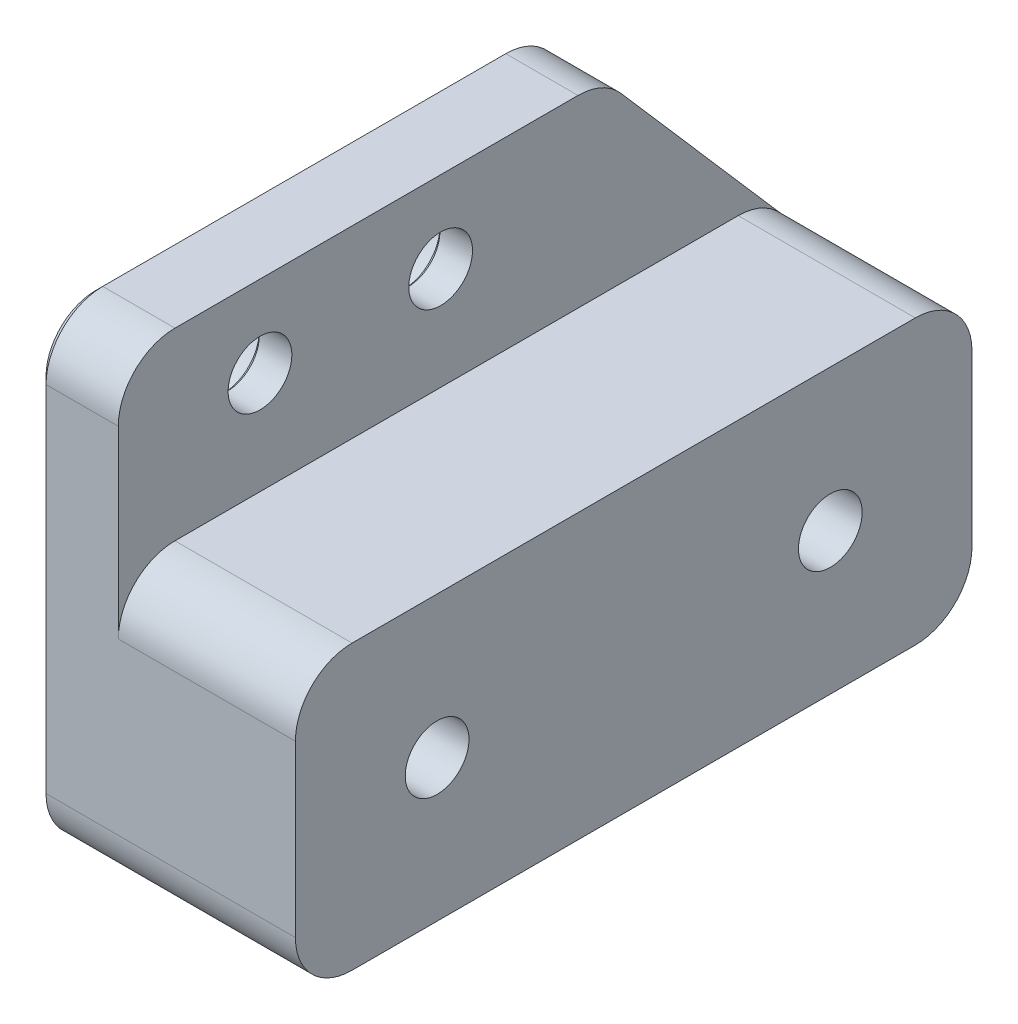
SolidWorks part; units mm, degrees
ref_plane "Front Plane" through (0, 0, 0) normal (0, 0, 1) x (1, 0, 0)
ref_plane "Top Plane" through (0, 0, 0) normal (0, 1, 0) x (1, 0, 0)
ref_plane "Right Plane" through (0, 0, 0) normal (1, 0, 0) x (0, 0, -1)
sketch "Sketch1" plane through (0, 0, 0) normal (1, 0, 0) x (0, 0, -1)
  line L0 (0, -10) -> (0, 23) construction
  line L1 (37.75, 0) -> (-10, 0) construction
  line L2 (-6, -10) -> (33.75, -10)
  line L3 (37.75, -6) -> (37.75, 6)
  line L4 (22.4457, 23) -> (-6, 23)
  line L6 (-10, 19) -> (-10, -6)
  line L7 (12.75, 17.25) -> (27.75, 0) construction
  line L8 (0, 17.25) -> (12.75, 17.25) construction
  line L9 (25.4641, 21.6247) -> (36.7684, 8.6247)
  circle A0 centre (0, 0) radius 2 construction
  circle A1 centre (0, 17.25) radius 2 construction
  circle A2 centre (27.75, 0) radius 2.25
  circle A3 centre (0, 17.25) radius 2.25
  circle A4 centre (0, 0) radius 2.25
  arc A5 (33.75, -10) -> (37.75, -6) centre (33.75, -6) ccw
  arc A7 (-6, 23) -> (-10, 19) centre (-6, 19) ccw
  arc A9 (-10, -6) -> (-6, -10) centre (-6, -6) ccw
  circle A10 centre (12.75, 17.25) radius 2.25
  arc A11 (22.4457, 23) -> (25.4641, 21.6247) centre (22.4457, 19) cw
  arc A12 (36.7684, 8.6247) -> (37.75, 6) centre (33.75, 6) cw
  point P35 (37.75, 0)
  dimension "D2" = 4
  dimension "D3" = 4
  dimension "D8" = 4
  dimension "D6" = 17.25
  dimension "D9" = 5.75
  dimension "D11" = 10
  dimension "D5" = 10
  dimension "D7" = 12.75
  dimension "D10" = 10
  dimension "D12" = 15
  dimension "D1" = 0.25
  dimension "D4" = 0.25
extrude "Boss-Extrude1" add sketch "Sketch1" along normal blind 2.6
sketch "Sketch3" plane through (0, 0, 0) normal (1, 0, 0) x (0, 0, -1)
  line L5 (-6, -10) -> (33.75, -10)
  line L6 (37.75, -6) -> (37.75, 6)
  line L7 (22.4457, 23) -> (-6, 23)
  line L8 (36.7684, 8.6247) -> (25.4641, 21.6247)
  line L9 (-10, 19) -> (-10, -6)
  line L10 (-6, -10) -> (33.75, -10)
  line L11 (37.75, -6) -> (37.75, 6)
  line L12 (22.4457, 23) -> (-6, 23)
  line L14 (-10, 19) -> (-10, -6)
  line L20 (36.7684, 8.6247) -> (25.4641, 21.6247)
  circle A0 centre (0, 0) radius 3.5 construction
  circle A1 centre (27.75, 0) radius 3.75
  circle A2 centre (27.75, 0) radius 2.25 construction
  circle A3 centre (0, 0) radius 2.25 construction
  circle A4 centre (0, 0) radius 3.75
  arc A5 (-10, -6) -> (-6, -10) centre (-6, -6) ccw
  arc A6 (33.75, -10) -> (37.75, -6) centre (33.75, -6) ccw
  arc A7 (37.75, 6) -> (36.7684, 8.6247) centre (33.75, 6) ccw
  arc A8 (-6, 23) -> (-10, 19) centre (-6, 19) ccw
  arc A9 (37.75, 6) -> (36.7684, 8.6247) centre (33.75, 6) ccw
  arc A10 (-10, -6) -> (-6, -10) centre (-6, -6) ccw
  arc A11 (33.75, -10) -> (37.75, -6) centre (33.75, -6) ccw
  arc A13 (-6, 23) -> (-10, 19) centre (-6, 19) ccw
  circle A15 centre (0, 17.25) radius 3.75
  circle A16 centre (0, 17.25) radius 2.25 construction
  circle A18 centre (12.75, 17.25) radius 3.75
  circle A19 centre (12.75, 17.25) radius 2.25 construction
  arc A22 (25.4641, 21.6247) -> (22.4457, 23) centre (22.4457, 19) ccw
  arc A23 (25.4641, 21.6247) -> (22.4457, 23) centre (22.4457, 19) ccw
  dimension "D2" = 7
  dimension "D3" = 0.25
extrude "Boss-Extrude3" add sketch "Sketch3" against normal blind 3
chamfer "Chamfer2" distance 0.3 angle 45 8 edges at (0, 0, -31.5) (0, 0, -30) (0, 0, -3.75) (0, 0, -2.25) (0, 17.25, -2.25) (0, 17.25, -3.75) (0, 17.25, -16.5) (0, 17.25, -15)
chamfer "Chamfer3" distance 0.5 angle 45 14 edges at (-3, 0, -3.75) (-3, 6.5, 10) (-3, 21.8284, 8.8284) (-3, 23, -8.2228) (-3, 0, -37.75) (-3, -8.8284, -36.5784) (-3, -10, -13.875) (-3, -8.8284, 8.8284) (-3, 0, -31.5) (-3, 17.25, -3.75) (-3, 7.4011, -37.4966) (-3, 15.1247, -31.1162) (-3, 22.64, -24.1041) (-3, 17.25, -16.5)
sketch "Sketch4" plane through (2.6, 0, 0) normal (1, 0, 0) x (0, 0, -1)
  line L0 (-6, -10) -> (33.75, -10) construction
  line L1 (-6, -10) -> (33.75, -10)
  line L2 (-25, 0) -> (10, 0) construction
  line L6 (37.75, -6) -> (37.75, 6)
  line L7 (-6, 10) -> (33.75, 10)
  line L8 (37.75, -6) -> (37.75, 6) construction
  line L9 (-10, -6) -> (-10, 6)
  line L10 (-10, 19) -> (-10, -6) construction
  circle A0 centre (0, 0) radius 2.25 construction
  circle A1 centre (27.75, 0) radius 2.25 construction
  arc A2 (33.75, -10) -> (37.75, -6) centre (33.75, -6) ccw construction
  arc A3 (-10, -6) -> (-6, -10) centre (-6, -6) ccw construction
  circle A4 centre (0, 0) radius 2.25
  circle A5 centre (27.75, 0) radius 2.25
  arc A6 (33.75, -10) -> (37.75, -6) centre (33.75, -6) ccw
  arc A7 (-10, -6) -> (-6, -10) centre (-6, -6) ccw
  arc A8 (-10, 6) -> (-6, 10) centre (-6, 6) cw
  arc A9 (37.75, 6) -> (33.75, 10) centre (33.75, 6) ccw
  arc A10 (37.75, 6) -> (36.7684, 8.6247) centre (33.75, 6) ccw construction
  dimension "D1" = 20
extrude "Boss-Extrude4" add sketch "Sketch4" along normal blind 12.5
equation "\"Tolerance\" = 0.25mm"
equation "\"D1@Sketch1\"=\"Tolerance\""
equation "\"D4@Sketch1\"=\"Tolerance\""
equation "\"Pocket_Head_M5\"= 8mm"
equation "\"Pocket_Head_M4\" = 7mm"
equation "\"D2@Sketch3\"=\"Pocket_Head_M4\""
equation "\"D3@Sketch3\"=\"Tolerance\""
equation "\"Pocket_Nut_M4\" = 7mm"
